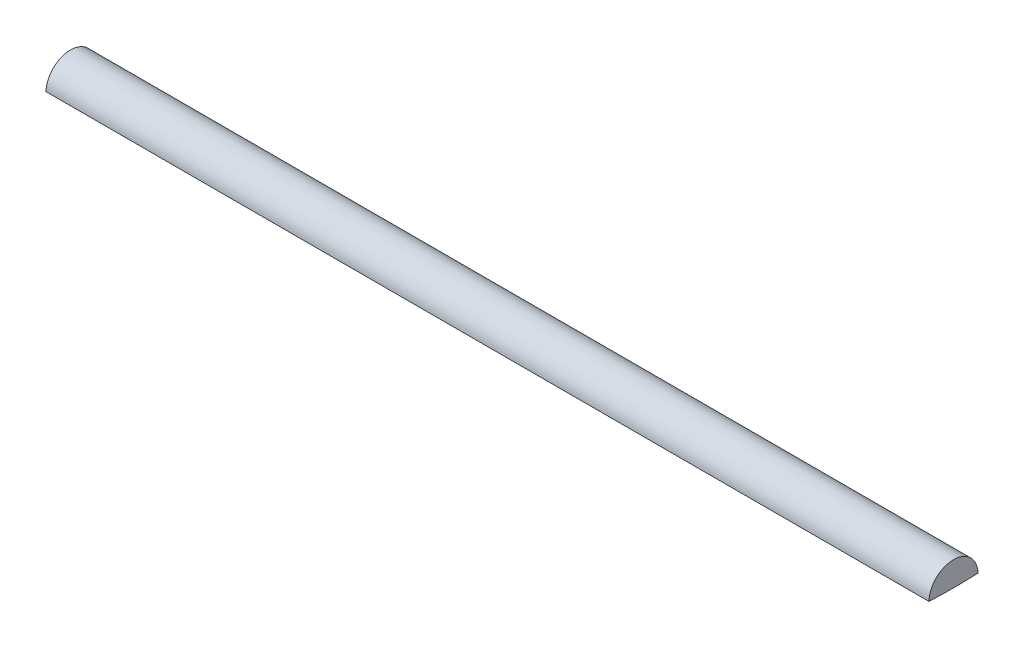
SolidWorks part; units mm, degrees
material "CMR DEFAULT - CHANGE MATERIAL"
ref_plane "XY PLANE - TOP" through (0, 0, 0) normal (0, 0, 1) x (1, 0, 0)
ref_plane "XZ PLANE - SIDE" through (0, 0, 0) normal (0, 1, 0) x (1, 0, 0)
ref_plane "YZ PLANE - FRONT" through (0, 0, 0) normal (1, 0, 0) x (0, 0, -1)
sketch "Sketch1" plane through (0, 0, 0) normal (1, 0, 0) x (0, 0, -1)
  arc A0 (-3.174, -63.4206) -> (3.174, -63.4206) centre (0, 0) ccw
  arc A1 (3.174, -63.4206) -> (-3.174, -63.4206) centre (0, -63.5) ccw
  dimension "D1" = 127
  dimension "D2" = 6.35
extrude "Boss-Extrude1" add sketch "Sketch1" along normal blind 114.3
